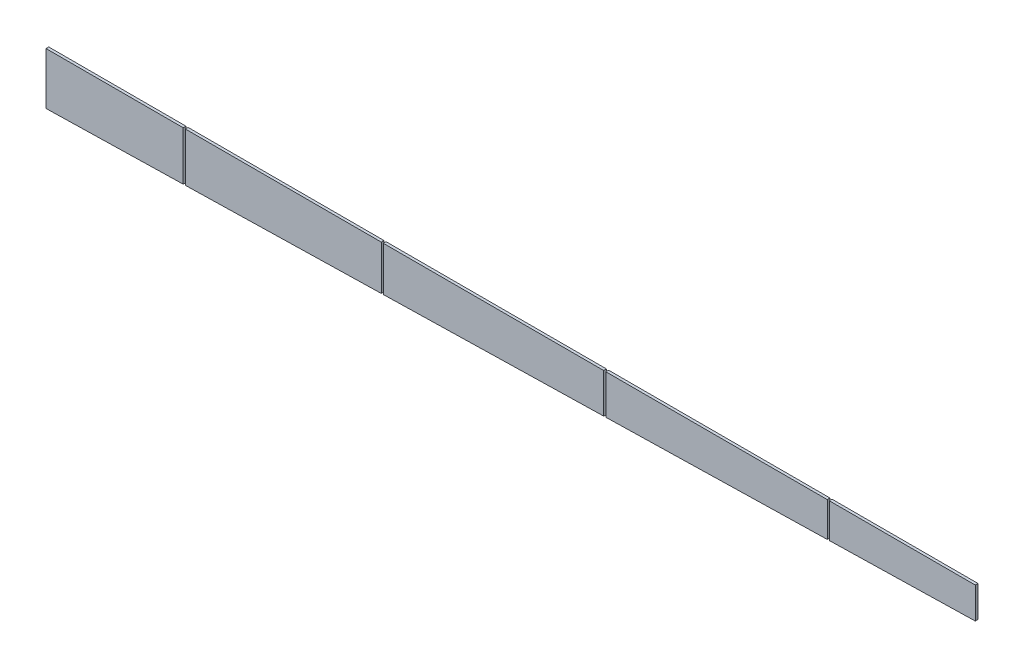
SolidWorks part; units mm, degrees
ref_plane "前视基准面" through (0, 0, 0) normal (0, 0, 1) x (1, 0, 0)
ref_plane "上视基准面" through (0, 0, 0) normal (0, 1, 0) x (1, 0, 0)
ref_plane "右视基准面" through (0, 0, 0) normal (1, 0, 0) x (0, 0, -1)
sketch "Model" plane through (0, 0, 0) normal (0, 0, 1) x (1, 0, 0)
  line L0 (443.7874, 361.8188) -> (443.7874, 323.8032)
  line L1 (443.7874, 323.8032) -> (544.2025, 326.0448)
  line L2 (544.2025, 326.0448) -> (544.2025, 361.8188)
  line L3 (544.2025, 361.8188) -> (443.7874, 361.8188)
  line L4 (545.7025, 361.8188) -> (545.7025, 326.0783)
  line L5 (545.7025, 326.0783) -> (689.1062, 329.2796)
  line L6 (689.1062, 329.2796) -> (689.1062, 361.8188)
  line L7 (689.1062, 361.8188) -> (545.7025, 361.8188)
  line L8 (690.6062, 361.8188) -> (690.6062, 329.3131)
  line L9 (690.6062, 329.3131) -> (851.8835, 332.9134)
  line L10 (851.8835, 332.9134) -> (851.8835, 361.8188)
  line L11 (851.8835, 361.8188) -> (690.6062, 361.8188)
  line L12 (853.3835, 361.8188) -> (853.3835, 332.9469)
  line L13 (853.3835, 332.9469) -> (1015.4416, 336.5646)
  line L14 (1015.4416, 336.5646) -> (1015.4416, 361.8188)
  line L15 (1015.4416, 361.8188) -> (853.3835, 361.8188)
  line L16 (1016.9416, 361.8188) -> (1016.9416, 336.5981)
  line L17 (1016.9416, 336.5981) -> (1123.7443, 338.9823)
  line L18 (1123.7443, 338.9823) -> (1123.7443, 361.8188)
  line L19 (1123.7443, 361.8188) -> (1016.9416, 361.8188)
extrude "凸台-拉伸1" add sketch "Model" along normal blind 2
